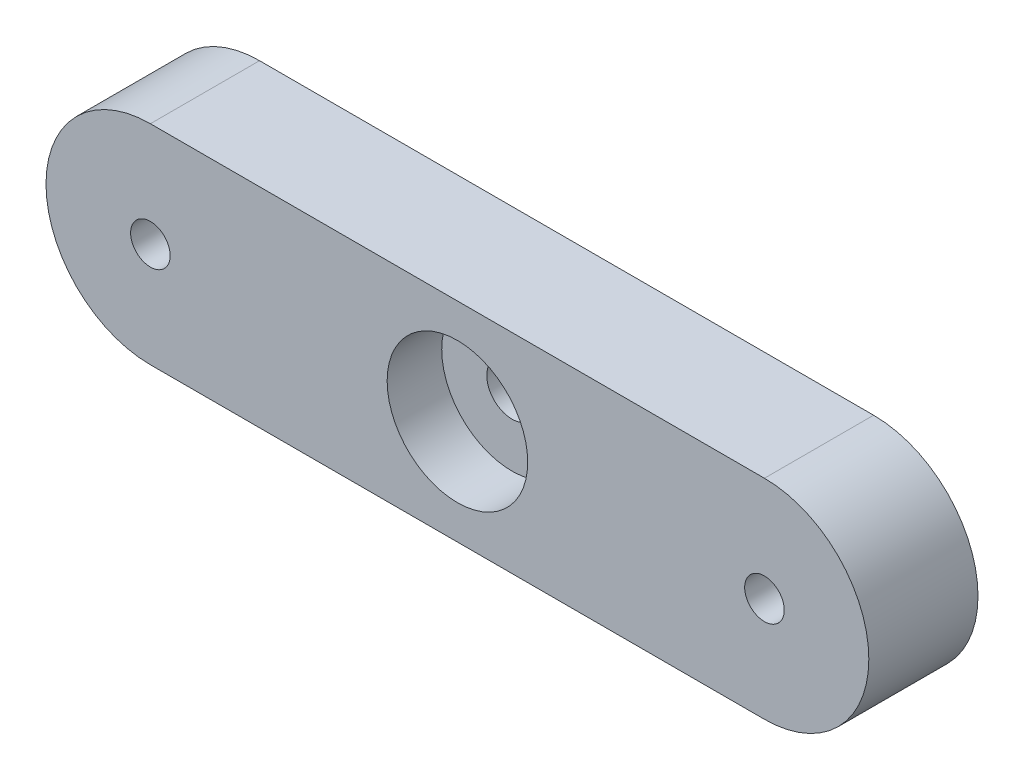
SolidWorks part; units mm, degrees
ref_plane "Спереди" through (0, 0, 0) normal (0, 0, 1) x (1, 0, 0)
ref_plane "Сверху" through (0, 0, 0) normal (0, 1, 0) x (1, 0, 0)
ref_plane "Справа" through (0, 0, 0) normal (1, 0, 0) x (0, 0, -1)
sketch "Эскиз1" plane through (0, 0, 0) normal (0, 0, 1) x (1, 0, 0)
  line L0 (0, 0) -> (45, 0) construction
  line L1 (0, 0) -> (45, 0) construction
  line L2 (0, 7.65) -> (45, 7.65)
  line L3 (0, -7.65) -> (45, -7.65)
  circle A0 centre (0, 0) radius 1.45
  circle A1 centre (45, 0) radius 1.45
  circle A2 centre (22.5, 0) radius 5.15
  arc A3 (0, 7.65) -> (0, -7.65) centre (0, 0) ccw
  arc A4 (45, -7.65) -> (45, 7.65) centre (45, 0) ccw
  point P7 (22.5, 0)
  dimension "D1" = 2.9
  dimension "D2" = 10.3
  dimension "D3" = 45
  dimension "D4" = 15.3
extrude "Бобышка-Вытянуть1" add sketch "Эскиз1" along normal blind 8
sketch "Эскиз2" plane through (0, 0, 0) normal (0, 0, -1) x (-1, 0, 0)
  circle A0 centre (-22.5, 0) radius 5.3054
  circle A1 centre (-22.5, 0) radius 1.85
  dimension "D1" = 3.7
extrude "Бобышка-Вытянуть2" add sketch "Эскиз2" against normal blind 4
